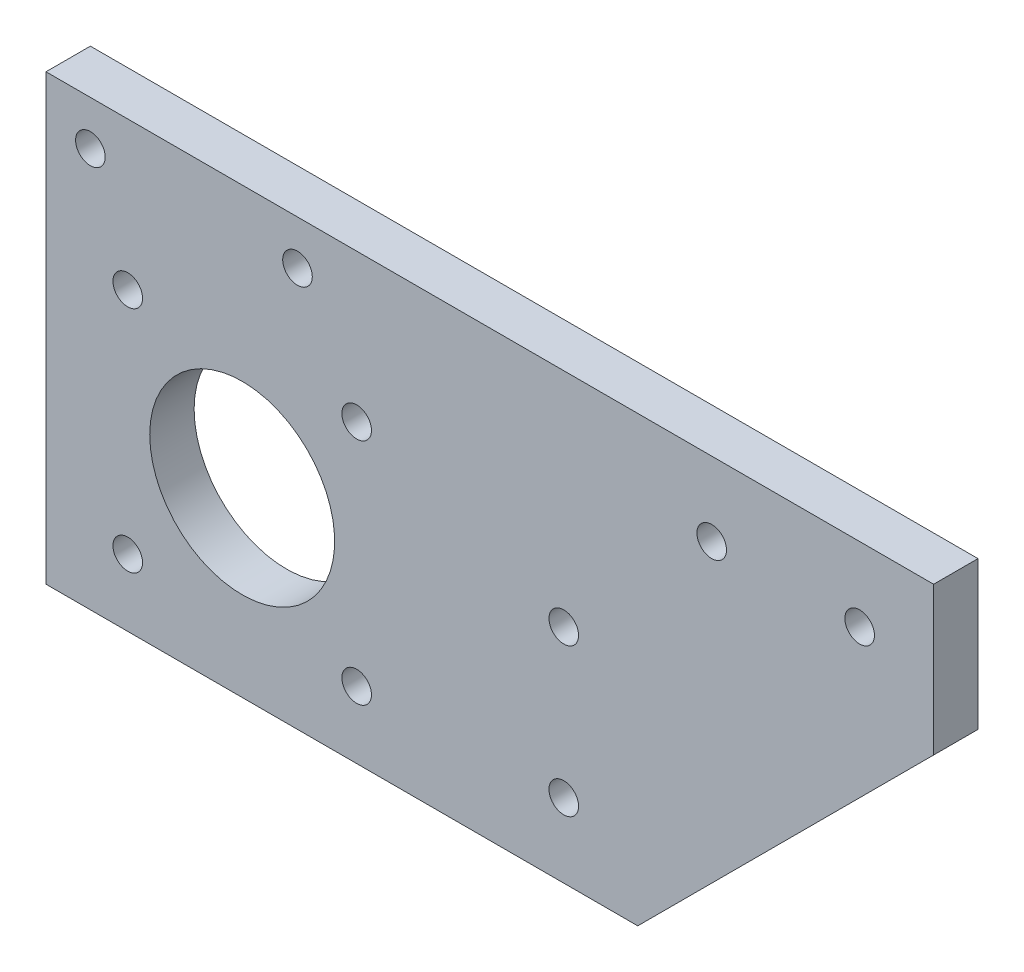
SolidWorks part; units mm, degrees
ref_plane "Front Plane" through (0, 0, 0) normal (0, 0, 1) x (1, 0, 0)
ref_plane "Top Plane" through (0, 0, 0) normal (0, 1, 0) x (1, 0, 0)
ref_plane "Right Plane" through (0, 0, 0) normal (1, 0, 0) x (0, 0, -1)
sketch "Sketch1" plane through (0, 0, 0) normal (0, 0, 1) x (1, 0, 0)
  line L0 (20, -60) -> (60, -20)
  line L1 (0, 0) -> (60, 0)
  line L2 (0, 0) -> (0, -60) construction
  line L3 (0, -60) -> (20, -60)
  line L4 (60, 0) -> (60, -20)
  line L5 (10, -60) -> (10, -50) construction
  line L6 (10, -50) -> (10, -30) construction
  line L7 (10, -30) -> (10, -10) construction
  line L8 (10, -10) -> (30, -10) construction
  line L9 (30, -10) -> (50, -10) construction
  line L10 (50, -10) -> (60, -10) construction
  line L11 (-60, 0) -> (-60, -6) construction
  line L12 (-60, -60) -> (0, -60)
  line L13 (-60, -60) -> (-60, 0)
  line L14 (-60, 0) -> (0, 0)
  line L15 (0, -60) -> (0, 0) construction
  line L16 (-60, -6) -> (-54, -6) construction
  line L17 (-60, 0) -> (-6, 0) construction
  line L18 (-6, 0) -> (-6, -6) construction
  line L19 (-6, -6) -> (-26, -6) construction
  circle A0 centre (50, -10) radius 2
  circle A1 centre (30, -10) radius 2
  circle A2 centre (10, -50) radius 2
  circle A3 centre (10, -30) radius 2
  circle A4 centre (-54, -6) radius 2
  circle A5 centre (-26, -6) radius 2
  dimension "D3" = 4
  dimension "D10" = 6
  dimension "D12" = 4
  dimension "D16" = 4
  dimension "D1" = 60
  dimension "D2" = 20
  dimension "D4" = 10
  dimension "D5" = 30
  dimension "D6" = 30
  dimension "D7" = 10
  dimension "D8" = 60
  dimension "D9" = 60
  dimension "D11" = 6
  dimension "D13" = 54
  dimension "D14" = 6
  dimension "D15" = 20
extrude "Boss-Extrude1" add sketch "Sketch1" along normal blind 6
sketch "Sketch2" plane through (0, 0, 0) normal (0, 0, -1) x (-1, 0, 0)
  line L0 (10, 0) -> (10, -6.7) construction
  line L1 (-60, 0) -> (60, 0) construction
  line L2 (10, 0) -> (18, 0) construction
  line L3 (18, 0) -> (18, -20) construction
  line L4 (18, -22) -> (18, -50.95) construction
  line L5 (18, -20) -> (48.95, -20) construction
  line L6 (18, -36.475) -> (33.475, -36.475) construction
  line L7 (33.475, -20) -> (33.475, -36.475) construction
  line L8 (46.95, -50.95) -> (20, -50.95) construction
  line L9 (33.475, -50.95) -> (33.475, -20) construction
  circle A0 centre (18, -20) radius 2
  circle A1 centre (18, -50.95) radius 2
  circle A2 centre (48.95, -20) radius 2
  circle A3 centre (48.95, -50.95) radius 2
  circle A4 centre (33.475, -35.475) radius 12.5
  point P14 (20, -20)
  point P16 (18, -48.95)
  dimension "D3" = 4
  dimension "D4" = 4
  dimension "D7" = 25
  dimension "D1" = 8
  dimension "D2" = 20
  dimension "D5" = 26.95
  dimension "D6" = 28.95
extrude "Cut-Extrude1" cut sketch "Sketch2" against normal blind 10
